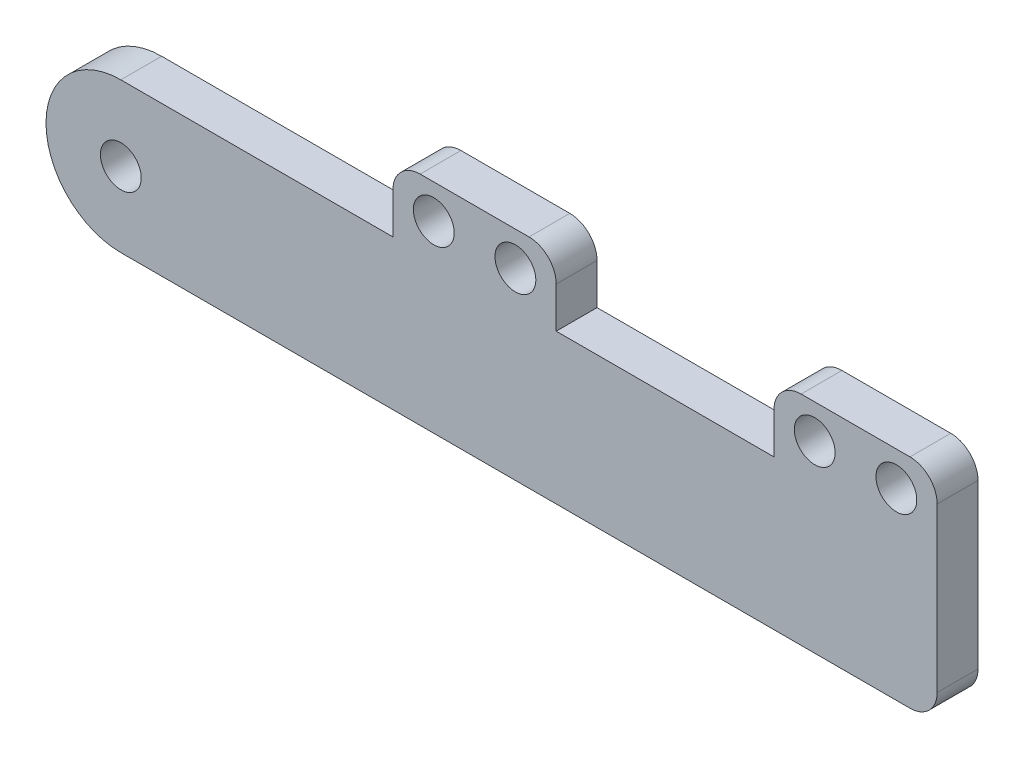
SolidWorks part; units mm, degrees
ref_plane "Plan de face" through (0, 0, 0) normal (0, 0, 1) x (1, 0, 0)
ref_plane "Plan de dessus" through (0, 0, 0) normal (0, 1, 0) x (1, 0, 0)
ref_plane "Plan de droite" through (0, 0, 0) normal (1, 0, 0) x (0, 0, -1)
sketch "Esquisse1" plane through (0, 0, 0) normal (0, 0, 1) x (1, 0, 0)
  line L0 (-22.9563, 0) -> (-22.9563, 5)
  line L1 (-22.9563, 5) -> (-10.9563, 5)
  line L2 (-10.9563, 5) -> (-10.9563, 0)
  line L3 (-10.9563, 0) -> (5.0437, 0)
  line L4 (5.0437, 0) -> (5.0437, 5)
  line L5 (5.0437, 5) -> (17.0437, 5)
  line L6 (17.0437, 5) -> (17.0437, -11)
  line L7 (-22.9563, 0) -> (-42.9563, 0)
  line L8 (17.0437, -11) -> (-42.9563, -11)
  line L9 (-16.9563, 5) -> (-16.9563, -2.8825) construction
  line L10 (-2.9563, 0) -> (-2.9563, 7.9951) construction
  arc A0 (-42.9563, -11) -> (-42.9563, 0) centre (-42.9563, -5.5) cw
  circle A1 centre (-19.9563, 2.5) radius 1.5
  circle A2 centre (-13.9563, 2.5) radius 1.5
  circle A3 centre (8.0437, 2.5) radius 1.5
  circle A4 centre (14.0437, 2.5) radius 1.5
  dimension "D8" = 5.5
  dimension "D9" = 3
  dimension "D10" = 2.5
  dimension "D11" = 3
  dimension "D1" = 5
  dimension "D2" = 12
  dimension "D3" = 12
  dimension "D4" = 16
  dimension "D5" = 16
  dimension "D6" = 60
  dimension "D7" = 20
extrude "Boss.-Extru.1" add sketch "Esquisse1" along normal blind 3
sketch "Esquisse2" plane through (0, 0, 3) normal (0, 0, 1) x (1, 0, 0)
  circle A0 centre (-42.9563, -5.5) radius 1.5
  dimension "D1" = 3
extrude "Enlèv. mat.-Extru.1" cut sketch "Esquisse2" against normal through all
fillet "Congé1" radius 2 5 edges at (17.0437, -11, 1.5) (17.0437, 5, 1.5) (5.0437, 5, 1.5) (-10.9563, 5, 1.5) (-22.9563, 5, 1.5)
